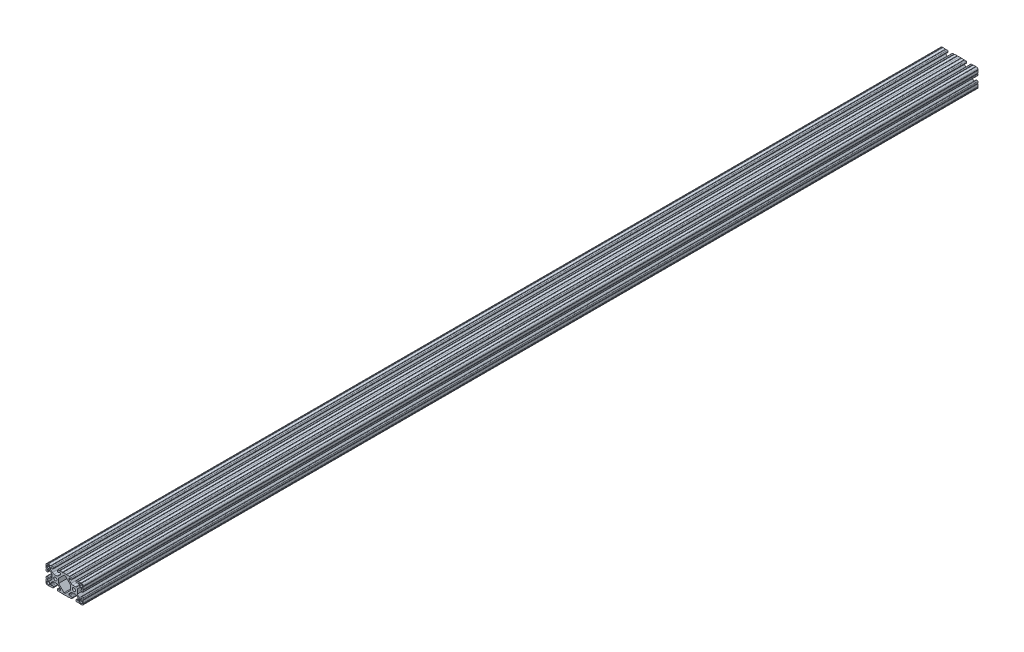
SolidWorks part; units mm, degrees
ref_plane "Front Plane" through (0, 0, 0) normal (0, 0, 1) x (1, 0, 0)
ref_plane "Top Plane" through (0, 0, 0) normal (0, 1, 0) x (1, 0, 0)
ref_plane "Right Plane" through (0, 0, 0) normal (1, 0, 0) x (0, 0, -1)
sketch "Sketch1" plane through (0, 0, 0) normal (0, 0, 1) x (1, 0, 0)
  line L0 (0, 19.05) -> (-19.1669, 19.05) construction
  line L1 (-6.7564, 0) -> (-6.7564, 4.6011)
  line L2 (-8.7357, 18.8026) -> (-15.7642, 19.0481) construction
  line L3 (-17.655, 18.5041) -> (-4.0303, 18.0283) construction
  line L4 (-5.5829, 18.6925) -> (-5.7212, 14.7325) construction
  line L5 (-11.8364, 17.2212) -> (-11.8364, 11.8364)
  line L6 (-2.6337, 6.7564) -> (0, 6.7564)
  line L7 (0, 0) -> (0, 19.05) construction
  line L8 (0, 0) -> (-19.1669, 0) construction
  line L9 (1.0776, 1.0776) -> (-1.0776, -1.0776) construction
  line L10 (-5.9923, 8.1476) -> (-9.915, 12.0703)
  line L11 (-6.7564, 4.6011) -> (-12.4423, 10.287)
  line L12 (-11.8364, 11.8364) -> (-17.2212, 11.8364)
  line L13 (0, 0) -> (-19.1669, 19.1669) construction
  line L14 (-15.7642, 19.0481) -> (-5.5829, 18.6925)
  line L15 (-4.064, 17.0637) -> (-4.0924, 16.2514)
  line L17 (-19.0481, 15.7642) -> (-18.6925, 5.5829)
  line L19 (-17.2212, 11.8364) -> (-17.2212, 14.4272)
  line L20 (-11.8364, 17.2212) -> (-14.4272, 17.2212)
  line L21 (-10.287, 12.9683) -> (-10.287, 14.3745)
  line L22 (-14.3745, 10.287) -> (-12.4423, 10.287)
  line L23 (-9.017, 15.6445) -> (-6.8707, 15.6445)
  line L24 (-6.8707, 15.6445) -> (-6.8707, 14.7325)
  line L25 (-5.7212, 14.7325) -> (-6.8707, 14.7325)
  line L26 (-17.0637, 4.064) -> (-16.2514, 4.0924)
  line L27 (-14.7325, 5.7212) -> (-14.7325, 6.8707)
  line L28 (-15.6445, 6.8707) -> (-14.7325, 6.8707)
  line L29 (-15.6445, 9.017) -> (-15.6445, 6.8707)
  circle A0 centre (0, 0) radius 3.3274
  arc A5 (-15.7642, 19.0481) -> (-19.0481, 15.7642) centre (-15.875, 15.875) ccw
  arc A7 (-9.3449, 18.8239) -> (-8.1264, 18.7813) centre (-8.7357, 18.8026) ccw
  arc A10 (-17.2212, 14.4272) -> (-14.4272, 17.2212) centre (-14.4272, 14.4272) cw
  arc A11 (-4.0924, 16.2514) -> (-5.7212, 14.7325) centre (-5.6662, 16.3064) cw
  arc A12 (-5.5829, 18.6925) -> (-4.064, 17.0637) centre (-5.6378, 17.1187) cw
  arc A13 (-5.9923, 8.1476) -> (-2.6337, 6.7564) centre (-2.6337, 11.5062) ccw
  arc A14 (-9.915, 12.0703) -> (-10.287, 12.9683) centre (-9.017, 12.9683) cw
  arc A15 (-10.287, 14.3745) -> (-9.017, 15.6445) centre (-9.017, 14.3745) cw
  arc A16 (-15.6949, 19.0456) -> (-14.4764, 19.0031) centre (-15.0857, 19.0244) ccw
  arc A17 (-18.6925, 5.5829) -> (-17.0637, 4.064) centre (-17.1187, 5.6378) ccw
  arc A18 (-16.2514, 4.0924) -> (-14.7325, 5.7212) centre (-16.3064, 5.6662) ccw
  arc A19 (-14.3745, 10.287) -> (-15.6445, 9.017) centre (-14.3745, 9.017) ccw
  arc A20 (-18.8239, 9.3449) -> (-18.7813, 8.1264) centre (-18.8026, 8.7357) cw
  arc A21 (-19.0456, 15.6949) -> (-19.0031, 14.4764) centre (-19.0244, 15.0857) cw
  point P27 (-5.7298, 13.1063)
  point P49 (-4.009, 18.6376)
  point P55 (-10.287, 12.4423)
  dimension "D1" = 6.6548
  dimension "D5" = 20.574
  dimension "D9" = 2
  dimension "D2" = 38.1
  dimension "D12" = 0.6096
  dimension "D10" = 3.175
  dimension "D13" = 2.794
  dimension "D14" = 7.2136
  dimension "D7" = 1.5748
  dimension "D20" = 4.7498
  dimension "D21" = 1.27
  dimension "D3" = 13.5128
  dimension "D4" = 13.5128
  dimension "D6" = 38.1
  dimension "D8" = 3.048
  dimension "D11" = 19.05
  dimension "D15" = 5.3848
  dimension "D16" = 3.9624
  dimension "D17" = 3.048
  dimension "D18" = 8.128
  dimension "D19" = 13.7414
  dimension "D22" = 10.3124
  dimension "D23" = 3.9624
sketch "Sketch3" plane through (0, 0, 0) normal (0, 0, 1) x (1, 0, 0)
  line L0 (0, 0) -> (19.05, 0) construction
  line L1 (19.05, 19.1628) -> (19.05, 15.6445) construction
  line L2 (15.7642, 19.0481) -> (19.05, 19.1628)
  line L3 (17.7998, 15.6445) -> (20.3002, 15.6445)
  line L4 (17.7998, -15.6445) -> (20.3002, -15.6445)
  line L5 (19.05, -15.6445) -> (19.05, -19.1628) construction
  line L6 (15.7642, -19.0481) -> (19.05, -19.1628)
  line L7 (40.7337, -6.7564) -> (35.4663, -6.7564)
  line L8 (-2.6337, 6.7564) -> (0, 6.7564) construction
  line L9 (-5.9923, 8.1476) -> (-9.915, 12.0703) construction
  line L10 (-10.287, 12.9683) -> (-10.287, 14.3745) construction
  line L11 (-9.017, 15.6445) -> (-6.8707, 15.6445) construction
  line L12 (-6.8707, 15.6445) -> (-6.8707, 14.7325) construction
  line L13 (-5.7212, 14.7325) -> (-6.8707, 14.7325) construction
  line L14 (-4.064, 17.0637) -> (-4.0924, 16.2514) construction
  line L15 (-15.7642, 19.0481) -> (-5.5829, 18.6925) construction
  line L16 (-19.0481, 15.7642) -> (-18.6925, 5.5829) construction
  line L17 (-17.0637, 4.064) -> (-16.2514, 4.0924) construction
  line L18 (-14.7325, 5.7212) -> (-14.7325, 6.8707) construction
  line L19 (-15.6445, 6.8707) -> (-14.7325, 6.8707) construction
  line L20 (-15.6445, 9.017) -> (-15.6445, 6.8707) construction
  line L21 (-14.3745, 10.287) -> (-12.4423, 10.287) construction
  line L22 (-6.7564, 4.6011) -> (-12.4423, 10.287) construction
  line L23 (-6.7564, 0) -> (-6.7564, 4.6011) construction
  line L24 (-2.6337, 6.7564) -> (2.6337, 6.7564)
  line L25 (-5.9923, 8.1476) -> (-9.915, 12.0703)
  line L26 (-10.287, 12.9683) -> (-10.287, 14.3745)
  line L27 (-9.017, 15.6445) -> (-6.8707, 15.6445)
  line L28 (-6.8707, 15.6445) -> (-6.8707, 14.7325)
  line L29 (-5.7212, 14.7325) -> (-6.8707, 14.7325)
  line L30 (-4.064, 17.0637) -> (-4.0924, 16.2514)
  line L31 (-15.7642, 19.0481) -> (-15.6949, 19.0456)
  line L32 (-19.0481, 15.7642) -> (-19.0456, 15.6949)
  line L33 (-17.0637, 4.064) -> (-16.2514, 4.0924)
  line L34 (-14.7325, 5.7212) -> (-14.7325, 6.8707)
  line L35 (-15.6445, 6.8707) -> (-14.7325, 6.8707)
  line L36 (-15.6445, 9.017) -> (-15.6445, 6.8707)
  line L37 (-14.3745, 10.287) -> (-12.4423, 10.287)
  line L38 (-6.7564, 4.6011) -> (-12.4423, 10.287)
  line L39 (-6.7564, -4.6011) -> (-6.7564, 4.6011)
  line L40 (0, 0) -> (-6.7564, 0) construction
  line L41 (0, 0) -> (0, 6.7564) construction
  line L42 (-8.1264, 18.7813) -> (-5.5829, 18.6925)
  line L43 (-14.4764, 19.0031) -> (-9.3449, 18.8239)
  line L44 (-11.8364, 11.8364) -> (-11.8364, 17.2212)
  line L45 (-17.2212, 11.8364) -> (-11.8364, 11.8364)
  line L46 (-17.2212, 14.4272) -> (-17.2212, 11.8364)
  line L47 (-11.8364, 17.2212) -> (-14.4272, 17.2212)
  line L48 (-11.8364, 11.8364) -> (-11.8364, 17.2212)
  line L49 (-17.2212, 11.8364) -> (-11.8364, 11.8364)
  line L50 (-17.2212, 14.4272) -> (-17.2212, 11.8364)
  line L51 (-11.8364, 17.2212) -> (-14.4272, 17.2212)
  line L52 (-19.0031, 14.4764) -> (-18.8239, 9.3449)
  line L53 (-18.7813, 8.1264) -> (-18.6925, 5.5829)
  line L54 (44.0923, -8.1476) -> (48.015, -12.0703)
  line L55 (48.387, -12.9683) -> (48.387, -14.3745)
  line L56 (47.117, -15.6445) -> (44.9707, -15.6445)
  line L57 (44.9707, -15.6445) -> (44.9707, -14.7325)
  line L58 (43.8212, -14.7325) -> (44.9707, -14.7325)
  line L59 (42.164, -17.0637) -> (42.1924, -16.2514)
  line L60 (14.4764, 19.0031) -> (9.3449, 18.8239)
  line L61 (8.1264, 18.7813) -> (5.5829, 18.6925)
  line L62 (6.7564, -4.6011) -> (6.7564, 4.6011)
  line L63 (6.7564, 4.6011) -> (17.7998, 15.6445)
  line L64 (53.8642, -19.0481) -> (53.7949, -19.0456)
  line L65 (57.1481, -15.7642) -> (57.1456, -15.6949)
  line L66 (55.1637, -4.064) -> (54.3514, -4.0924)
  line L67 (52.8325, -5.7212) -> (52.8325, -6.8707)
  line L68 (53.7445, -6.8707) -> (52.8325, -6.8707)
  line L69 (53.7445, -9.017) -> (53.7445, -6.8707)
  line L70 (15.7642, 19.0481) -> (15.6949, 19.0456)
  line L71 (4.064, 17.0637) -> (4.0924, 16.2514)
  line L72 (5.7212, 14.7325) -> (6.8707, 14.7325)
  line L73 (6.8707, 15.6445) -> (6.8707, 14.7325)
  line L74 (9.017, 15.6445) -> (6.8707, 15.6445)
  line L75 (10.287, 12.9683) -> (10.287, 14.3745)
  line L76 (5.9923, 8.1476) -> (9.915, 12.0703)
  line L77 (5.9923, -8.1476) -> (9.915, -12.0703)
  line L78 (10.287, -12.9683) -> (10.287, -14.3745)
  line L79 (9.017, -15.6445) -> (6.8707, -15.6445)
  line L80 (6.8707, -15.6445) -> (6.8707, -14.7325)
  line L81 (5.7212, -14.7325) -> (6.8707, -14.7325)
  line L82 (4.064, -17.0637) -> (4.0924, -16.2514)
  line L83 (15.7642, -19.0481) -> (15.6949, -19.0456)
  line L84 (52.4745, -10.287) -> (50.5423, -10.287)
  line L85 (44.8564, -4.6011) -> (50.5423, -10.287)
  line L86 (46.2264, -18.7813) -> (43.6829, -18.6925)
  line L87 (52.5764, -19.0031) -> (47.4449, -18.8239)
  line L88 (49.9364, -11.8364) -> (49.9364, -17.2212)
  line L89 (55.3212, -11.8364) -> (49.9364, -11.8364)
  line L90 (6.7564, -4.6011) -> (17.7998, -15.6445)
  line L91 (8.1264, -18.7813) -> (5.5829, -18.6925)
  line L92 (14.4764, -19.0031) -> (9.3449, -18.8239)
  line L93 (55.3212, -14.4272) -> (55.3212, -11.8364)
  line L94 (49.9364, -17.2212) -> (52.5272, -17.2212)
  line L95 (57.1031, -14.4764) -> (56.9239, -9.3449)
  line L96 (56.8813, -8.1264) -> (56.7925, -5.5829)
  line L97 (23.6236, -19.0031) -> (28.7551, -18.8239)
  line L98 (29.9736, -18.7813) -> (32.5171, -18.6925)
  line L99 (-18.7813, -8.1264) -> (-18.6925, -5.5829)
  line L100 (-19.0031, -14.4764) -> (-18.8239, -9.3449)
  line L101 (-11.8364, -17.2212) -> (-14.4272, -17.2212)
  line L102 (-17.2212, -14.4272) -> (-17.2212, -11.8364)
  line L103 (-17.2212, -11.8364) -> (-11.8364, -11.8364)
  line L104 (-11.8364, -11.8364) -> (-11.8364, -17.2212)
  line L105 (-14.4764, -19.0031) -> (-9.3449, -18.8239)
  line L106 (-8.1264, -18.7813) -> (-5.5829, -18.6925)
  line L107 (-6.7564, -4.6011) -> (-12.4423, -10.287)
  line L108 (-14.3745, -10.287) -> (-12.4423, -10.287)
  line L109 (-15.6445, -9.017) -> (-15.6445, -6.8707)
  line L110 (-15.6445, -6.8707) -> (-14.7325, -6.8707)
  line L111 (-14.7325, -5.7212) -> (-14.7325, -6.8707)
  line L112 (-17.0637, -4.064) -> (-16.2514, -4.0924)
  line L113 (-19.0481, -15.7642) -> (-19.0456, -15.6949)
  line L114 (-15.7642, -19.0481) -> (-15.6949, -19.0456)
  line L115 (-4.064, -17.0637) -> (-4.0924, -16.2514)
  line L116 (-5.7212, -14.7325) -> (-6.8707, -14.7325)
  line L117 (-6.8707, -15.6445) -> (-6.8707, -14.7325)
  line L118 (-9.017, -15.6445) -> (-6.8707, -15.6445)
  line L119 (-10.287, -12.9683) -> (-10.287, -14.3745)
  line L120 (-5.9923, -8.1476) -> (-9.915, -12.0703)
  line L121 (-2.6337, -6.7564) -> (2.6337, -6.7564)
  line L122 (31.3436, -4.6011) -> (20.3002, -15.6445)
  line L123 (22.3358, -19.0481) -> (22.4051, -19.0456)
  line L124 (34.036, -17.0637) -> (34.0076, -16.2514)
  line L125 (32.3788, -14.7325) -> (31.2293, -14.7325)
  line L126 (31.2293, -15.6445) -> (31.2293, -14.7325)
  line L127 (29.083, -15.6445) -> (31.2293, -15.6445)
  line L128 (27.813, -12.9683) -> (27.813, -14.3745)
  line L129 (32.1077, -8.1476) -> (28.185, -12.0703)
  line L130 (32.1077, 8.1476) -> (28.185, 12.0703)
  line L131 (27.813, 12.9683) -> (27.813, 14.3745)
  line L132 (29.083, 15.6445) -> (31.2293, 15.6445)
  line L133 (31.2293, 15.6445) -> (31.2293, 14.7325)
  line L134 (32.3788, 14.7325) -> (31.2293, 14.7325)
  line L135 (34.036, 17.0637) -> (34.0076, 16.2514)
  line L136 (22.3358, 19.0481) -> (22.4051, 19.0456)
  line L137 (31.3436, 4.6011) -> (20.3002, 15.6445)
  line L138 (31.3436, -4.6011) -> (31.3436, 4.6011)
  line L139 (29.9736, 18.7813) -> (32.5171, 18.6925)
  line L140 (23.6236, 19.0031) -> (28.7551, 18.8239)
  line L141 (56.8813, 8.1264) -> (56.7925, 5.5829)
  line L142 (57.1031, 14.4764) -> (56.9239, 9.3449)
  line L143 (49.9364, 17.2212) -> (52.5272, 17.2212)
  line L144 (55.3212, 14.4272) -> (55.3212, 11.8364)
  line L145 (55.3212, 11.8364) -> (49.9364, 11.8364)
  line L146 (49.9364, 11.8364) -> (49.9364, 17.2212)
  line L147 (52.5764, 19.0031) -> (47.4449, 18.8239)
  line L148 (46.2264, 18.7813) -> (43.6829, 18.6925)
  line L149 (44.8564, -4.6011) -> (44.8564, 4.6011)
  line L150 (44.8564, 4.6011) -> (50.5423, 10.287)
  line L151 (52.4745, 10.287) -> (50.5423, 10.287)
  line L152 (53.7445, 9.017) -> (53.7445, 6.8707)
  line L153 (53.7445, 6.8707) -> (52.8325, 6.8707)
  line L154 (52.8325, 5.7212) -> (52.8325, 6.8707)
  line L155 (55.1637, 4.064) -> (54.3514, 4.0924)
  line L156 (57.1481, 15.7642) -> (57.1456, 15.6949)
  line L157 (53.8642, 19.0481) -> (53.7949, 19.0456)
  line L158 (42.164, 17.0637) -> (42.1924, 16.2514)
  line L159 (43.8212, 14.7325) -> (44.9707, 14.7325)
  line L160 (44.9707, 15.6445) -> (44.9707, 14.7325)
  line L161 (47.117, 15.6445) -> (44.9707, 15.6445)
  line L162 (48.387, 12.9683) -> (48.387, 14.3745)
  line L163 (44.0923, 8.1476) -> (48.015, 12.0703)
  line L164 (40.7337, 6.7564) -> (35.4663, 6.7564)
  line L165 (22.3358, -19.0481) -> (19.05, -19.1628)
  line L166 (22.3358, 19.0481) -> (19.05, 19.1628)
  arc A0 (53.7949, -19.0456) -> (52.5764, -19.0031) centre (53.1857, -19.0244) ccw
  arc A1 (44.0923, -8.1476) -> (40.7337, -6.7564) centre (40.7337, -11.5062) ccw
  arc A2 (48.387, -12.9683) -> (48.015, -12.0703) centre (47.117, -12.9683) ccw
  arc A3 (47.117, -15.6445) -> (48.387, -14.3745) centre (47.117, -14.3745) ccw
  arc A4 (43.8212, -14.7325) -> (42.1924, -16.2514) centre (43.7662, -16.3064) ccw
  arc A5 (42.164, -17.0637) -> (43.6829, -18.6925) centre (43.7378, -17.1187) ccw
  arc A6 (53.8642, -19.0481) -> (57.1481, -15.7642) centre (53.975, -15.875) ccw
  arc A7 (56.7925, -5.5829) -> (55.1637, -4.064) centre (55.2187, -5.6378) ccw
  arc A8 (54.3514, -4.0924) -> (52.8325, -5.7212) centre (54.4064, -5.6662) ccw
  arc A9 (-15.6949, 19.0456) -> (-14.4764, 19.0031) centre (-15.0857, 19.0244) ccw construction
  arc A10 (-5.9923, 8.1476) -> (-2.6337, 6.7564) centre (-2.6337, 11.5062) ccw construction
  arc A11 (-10.287, 12.9683) -> (-9.915, 12.0703) centre (-9.017, 12.9683) ccw construction
  arc A12 (-9.017, 15.6445) -> (-10.287, 14.3745) centre (-9.017, 14.3745) ccw construction
  arc A13 (-5.7212, 14.7325) -> (-4.0924, 16.2514) centre (-5.6662, 16.3064) ccw construction
  arc A14 (-4.064, 17.0637) -> (-5.5829, 18.6925) centre (-5.6378, 17.1187) ccw construction
  arc A15 (-15.7642, 19.0481) -> (-19.0481, 15.7642) centre (-15.875, 15.875) ccw construction
  arc A16 (-18.6925, 5.5829) -> (-17.0637, 4.064) centre (-17.1187, 5.6378) ccw construction
  arc A17 (-16.2514, 4.0924) -> (-14.7325, 5.7212) centre (-16.3064, 5.6662) ccw construction
  arc A18 (-14.3745, 10.287) -> (-15.6445, 9.017) centre (-14.3745, 9.017) ccw construction
  arc A19 (-9.3449, 18.8239) -> (-8.1264, 18.7813) centre (-8.7357, 18.8026) ccw construction
  arc A20 (-18.7813, 8.1264) -> (-18.8239, 9.3449) centre (-18.8026, 8.7357) ccw construction
  arc A21 (-19.0031, 14.4764) -> (-19.0456, 15.6949) centre (-19.0244, 15.0857) ccw construction
  arc A22 (-15.6949, 19.0456) -> (-14.4764, 19.0031) centre (-15.0857, 19.0244) ccw
  arc A23 (-5.9923, 8.1476) -> (-2.6337, 6.7564) centre (-2.6337, 11.5062) ccw
  arc A24 (-10.287, 12.9683) -> (-9.915, 12.0703) centre (-9.017, 12.9683) ccw
  arc A25 (-9.017, 15.6445) -> (-10.287, 14.3745) centre (-9.017, 14.3745) ccw
  arc A26 (-5.7212, 14.7325) -> (-4.0924, 16.2514) centre (-5.6662, 16.3064) ccw
  arc A27 (-4.064, 17.0637) -> (-5.5829, 18.6925) centre (-5.6378, 17.1187) ccw
  arc A28 (-15.7642, 19.0481) -> (-19.0481, 15.7642) centre (-15.875, 15.875) ccw
  arc A29 (-18.6925, 5.5829) -> (-17.0637, 4.064) centre (-17.1187, 5.6378) ccw
  arc A30 (-16.2514, 4.0924) -> (-14.7325, 5.7212) centre (-16.3064, 5.6662) ccw
  arc A31 (-14.3745, 10.287) -> (-15.6445, 9.017) centre (-14.3745, 9.017) ccw
  arc A32 (-9.3449, 18.8239) -> (-8.1264, 18.7813) centre (-8.7357, 18.8026) ccw
  arc A33 (-18.7813, 8.1264) -> (-18.8239, 9.3449) centre (-18.8026, 8.7357) ccw
  arc A34 (-19.0031, 14.4764) -> (-19.0456, 15.6949) centre (-19.0244, 15.0857) ccw
  arc A35 (52.4745, -10.287) -> (53.7445, -9.017) centre (52.4745, -9.017) ccw
  circle A36 centre (0, 0) radius 3.3274
  circle A37 centre (0, 0) radius 3.3274
  arc A38 (-14.4272, 17.2212) -> (-17.2212, 14.4272) centre (-14.4272, 14.4272) ccw
  arc A39 (-14.4272, 17.2212) -> (-17.2212, 14.4272) centre (-14.4272, 14.4272) ccw
  arc A40 (47.4449, -18.8239) -> (46.2264, -18.7813) centre (46.8357, -18.8026) ccw
  arc A41 (56.8813, -8.1264) -> (56.9239, -9.3449) centre (56.9026, -8.7357) ccw
  arc A42 (9.3449, 18.8239) -> (8.1264, 18.7813) centre (8.7357, 18.8026) cw
  arc A43 (57.1031, -14.4764) -> (57.1456, -15.6949) centre (57.1244, -15.0857) ccw
  arc A44 (52.5272, -17.2212) -> (55.3212, -14.4272) centre (52.5272, -14.4272) ccw
  arc A45 (28.7551, -18.8239) -> (29.9736, -18.7813) centre (29.3643, -18.8026) cw
  arc A46 (34.036, -17.0637) -> (32.5171, -18.6925) centre (32.4622, -17.1187) cw
  arc A47 (4.064, 17.0637) -> (5.5829, 18.6925) centre (5.6378, 17.1187) cw
  arc A48 (5.7212, 14.7325) -> (4.0924, 16.2514) centre (5.6662, 16.3064) cw
  arc A49 (9.017, 15.6445) -> (10.287, 14.3745) centre (9.017, 14.3745) cw
  arc A50 (10.287, 12.9683) -> (9.915, 12.0703) centre (9.017, 12.9683) cw
  arc A51 (5.9923, 8.1476) -> (2.6337, 6.7564) centre (2.6337, 11.5062) cw
  arc A52 (15.6949, 19.0456) -> (14.4764, 19.0031) centre (15.0857, 19.0244) cw
  arc A53 (32.3788, -14.7325) -> (34.0076, -16.2514) centre (32.4338, -16.3064) cw
  arc A54 (15.6949, -19.0456) -> (14.4764, -19.0031) centre (15.0857, -19.0244) ccw
  arc A55 (5.9923, -8.1476) -> (2.6337, -6.7564) centre (2.6337, -11.5062) ccw
  arc A56 (10.287, -12.9683) -> (9.915, -12.0703) centre (9.017, -12.9683) ccw
  arc A57 (9.017, -15.6445) -> (10.287, -14.3745) centre (9.017, -14.3745) ccw
  arc A58 (5.7212, -14.7325) -> (4.0924, -16.2514) centre (5.6662, -16.3064) ccw
  arc A59 (4.064, -17.0637) -> (5.5829, -18.6925) centre (5.6378, -17.1187) ccw
  arc A60 (29.083, -15.6445) -> (27.813, -14.3745) centre (29.083, -14.3745) cw
  arc A61 (27.813, -12.9683) -> (28.185, -12.0703) centre (29.083, -12.9683) cw
  arc A62 (32.1077, -8.1476) -> (35.4663, -6.7564) centre (35.4663, -11.5062) cw
  arc A63 (22.4051, -19.0456) -> (23.6236, -19.0031) centre (23.0143, -19.0244) cw
  arc A64 (9.3449, -18.8239) -> (8.1264, -18.7813) centre (8.7357, -18.8026) ccw
  arc A65 (22.4051, 19.0456) -> (23.6236, 19.0031) centre (23.0143, 19.0244) ccw
  arc A66 (32.1077, 8.1476) -> (35.4663, 6.7564) centre (35.4663, 11.5062) ccw
  arc A67 (-14.4272, -17.2212) -> (-17.2212, -14.4272) centre (-14.4272, -14.4272) cw
  arc A68 (27.813, 12.9683) -> (28.185, 12.0703) centre (29.083, 12.9683) ccw
  arc A69 (-19.0031, -14.4764) -> (-19.0456, -15.6949) centre (-19.0244, -15.0857) cw
  arc A70 (-18.7813, -8.1264) -> (-18.8239, -9.3449) centre (-18.8026, -8.7357) cw
  arc A71 (-9.3449, -18.8239) -> (-8.1264, -18.7813) centre (-8.7357, -18.8026) cw
  arc A72 (-14.3745, -10.287) -> (-15.6445, -9.017) centre (-14.3745, -9.017) cw
  arc A73 (-16.2514, -4.0924) -> (-14.7325, -5.7212) centre (-16.3064, -5.6662) cw
  arc A74 (-18.6925, -5.5829) -> (-17.0637, -4.064) centre (-17.1187, -5.6378) cw
  arc A75 (-15.7642, -19.0481) -> (-19.0481, -15.7642) centre (-15.875, -15.875) cw
  arc A76 (-4.064, -17.0637) -> (-5.5829, -18.6925) centre (-5.6378, -17.1187) cw
  arc A77 (-5.7212, -14.7325) -> (-4.0924, -16.2514) centre (-5.6662, -16.3064) cw
  arc A78 (-9.017, -15.6445) -> (-10.287, -14.3745) centre (-9.017, -14.3745) cw
  arc A79 (-10.287, -12.9683) -> (-9.915, -12.0703) centre (-9.017, -12.9683) cw
  arc A80 (-5.9923, -8.1476) -> (-2.6337, -6.7564) centre (-2.6337, -11.5062) cw
  arc A81 (-15.6949, -19.0456) -> (-14.4764, -19.0031) centre (-15.0857, -19.0244) cw
  arc A82 (29.083, 15.6445) -> (27.813, 14.3745) centre (29.083, 14.3745) ccw
  arc A83 (32.3788, 14.7325) -> (34.0076, 16.2514) centre (32.4338, 16.3064) ccw
  arc A84 (34.036, 17.0637) -> (32.5171, 18.6925) centre (32.4622, 17.1187) ccw
  arc A85 (28.7551, 18.8239) -> (29.9736, 18.7813) centre (29.3643, 18.8026) ccw
  arc A86 (52.5272, 17.2212) -> (55.3212, 14.4272) centre (52.5272, 14.4272) cw
  circle A87 centre (38.1, 0) radius 3.3274
  arc A88 (57.1031, 14.4764) -> (57.1456, 15.6949) centre (57.1244, 15.0857) cw
  arc A89 (56.8813, 8.1264) -> (56.9239, 9.3449) centre (56.9026, 8.7357) cw
  arc A90 (47.4449, 18.8239) -> (46.2264, 18.7813) centre (46.8357, 18.8026) cw
  arc A91 (52.4745, 10.287) -> (53.7445, 9.017) centre (52.4745, 9.017) cw
  arc A92 (54.3514, 4.0924) -> (52.8325, 5.7212) centre (54.4064, 5.6662) cw
  arc A93 (56.7925, 5.5829) -> (55.1637, 4.064) centre (55.2187, 5.6378) cw
  arc A94 (53.8642, 19.0481) -> (57.1481, 15.7642) centre (53.975, 15.875) cw
  arc A95 (42.164, 17.0637) -> (43.6829, 18.6925) centre (43.7378, 17.1187) cw
  arc A96 (43.8212, 14.7325) -> (42.1924, 16.2514) centre (43.7662, 16.3064) cw
  arc A97 (47.117, 15.6445) -> (48.387, 14.3745) centre (47.117, 14.3745) cw
  arc A98 (48.387, 12.9683) -> (48.015, 12.0703) centre (47.117, 12.9683) cw
  arc A99 (44.0923, 8.1476) -> (40.7337, 6.7564) centre (40.7337, 11.5062) cw
  arc A100 (53.7949, 19.0456) -> (52.5764, 19.0031) centre (53.1857, 19.0244) cw
  point P201 (6.7564, 0)
  point P293 (31.3436, 0)
  dimension "D2" = 3.048
  dimension "D3" = 19.05
  dimension "D1" = 0
extrude "Extrude1" add sketch "Sketch3" along normal mid plane 1828.8
equation "\"D11@Sketch1\" = \"D6@Sketch1\"/2"
equation "\"D2@Sketch3\" = \"D8@Sketch1\"*1"
equation "\"D16@Sketch1\" = \"D8@Sketch1\"*1.3"
equation "\"D17@Sketch1\" = \"D8@Sketch1\""
equation "\"D12@Sketch1\" = \"D8@Sketch1\"/5"
